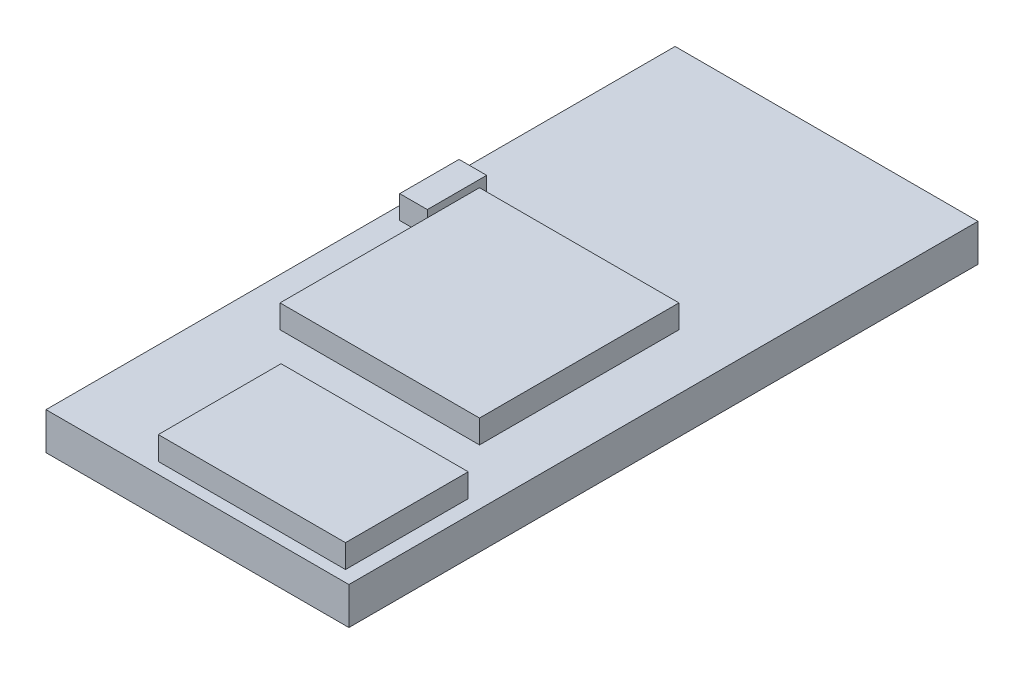
SolidWorks part; units mm, degrees
ref_plane "前视基准面" through (0, 0, 0) normal (0, 0, 1) x (1, 0, 0)
ref_plane "上视基准面" through (0, 0, 0) normal (0, 1, 0) x (1, 0, 0)
ref_plane "右视基准面" through (0, 0, 0) normal (1, 0, 0) x (0, 0, -1)
sketch "草图1" plane through (0, 0, 0) normal (0, 1, 0) x (1, 0, 0)
  line L0 (0, 18.0542) -> (0, -28.7617) construction
  line L1 (-6.5, 13.5) -> (6.5, 13.5)
  line L2 (-6.5, 13.5) -> (-6.5, -13.5)
  line L3 (-6.5, -13.5) -> (6.5, -13.5)
  line L4 (6.5, 13.5) -> (6.5, -13.5)
  line L5 (-12.651, 0) -> (17.9942, 0) construction
  dimension "D1" = 13
  dimension "D2" = 27
extrude "凸台-拉伸1" add sketch "草图1" along normal blind 1.6
sketch "草图2" plane through (0, 1.6, 0) normal (0, 1, 0) x (1, 0, 0)
  line L1 (5.8706, -13.0167) -> (-2.1633, -13.0167)
  line L2 (5.8706, -13.0167) -> (5.8706, -7.7486)
  line L3 (5.8706, -7.7486) -> (-2.1633, -7.7486)
  line L4 (-2.1633, -13.0167) -> (-2.1633, -7.7486)
  line L5 (4.1145, -5.5096) -> (-4.4462, -5.5096)
  line L6 (4.1145, -5.5096) -> (4.1145, 3.0511)
  line L7 (4.1145, 3.0511) -> (-4.4462, 3.0511)
  line L8 (-4.4462, -5.5096) -> (-4.4462, 3.0511)
  line L9 (-5.9388, 3.6657) -> (-4.7535, 3.6657)
  line L10 (-5.9388, 3.6657) -> (-5.9388, 1.1195)
  line L11 (-5.9388, 1.1195) -> (-4.7535, 1.1195)
  line L12 (-4.7535, 3.6657) -> (-4.7535, 1.1195)
extrude "凸台-拉伸2" add sketch "草图2" along normal blind 1
sketch "草图3" plane through (0, 1.6, 0) normal (0, 1, 0) x (1, 0, 0)
  line L0 (4.456, 6.6949) -> (4.456, 12.2265)
  line L1 (4.456, 12.2265) -> (2.7877, 12.2265)
  line L2 (2.7877, 12.2265) -> (2.7877, 8.4949)
  line L3 (2.7877, 8.4949) -> (1.2073, 8.4949)
  line L4 (1.2073, 8.4949) -> (1.2073, 12.2265)
  line L5 (1.2073, 12.2265) -> (-0.5927, 12.2265)
  line L6 (-0.5927, 12.2265) -> (-0.5927, 8.4949)
  line L7 (-0.5927, 8.4949) -> (-2.217, 8.4949)
  line L8 (-2.217, 8.4949) -> (-2.217, 12.2265)
  line L9 (-2.217, 12.2265) -> (-3.7536, 12.2265)
  line L10 (-3.7536, 12.2265) -> (-3.7536, 8.4949)
  line L11 (-3.7536, 8.4949) -> (-5.4657, 8.4949)
  line L12 (-5.4657, 8.4949) -> (-5.4657, 12.2265)
  line L13 (-5.4657, 12.2265) -> (-6.0803, 12.2265)
